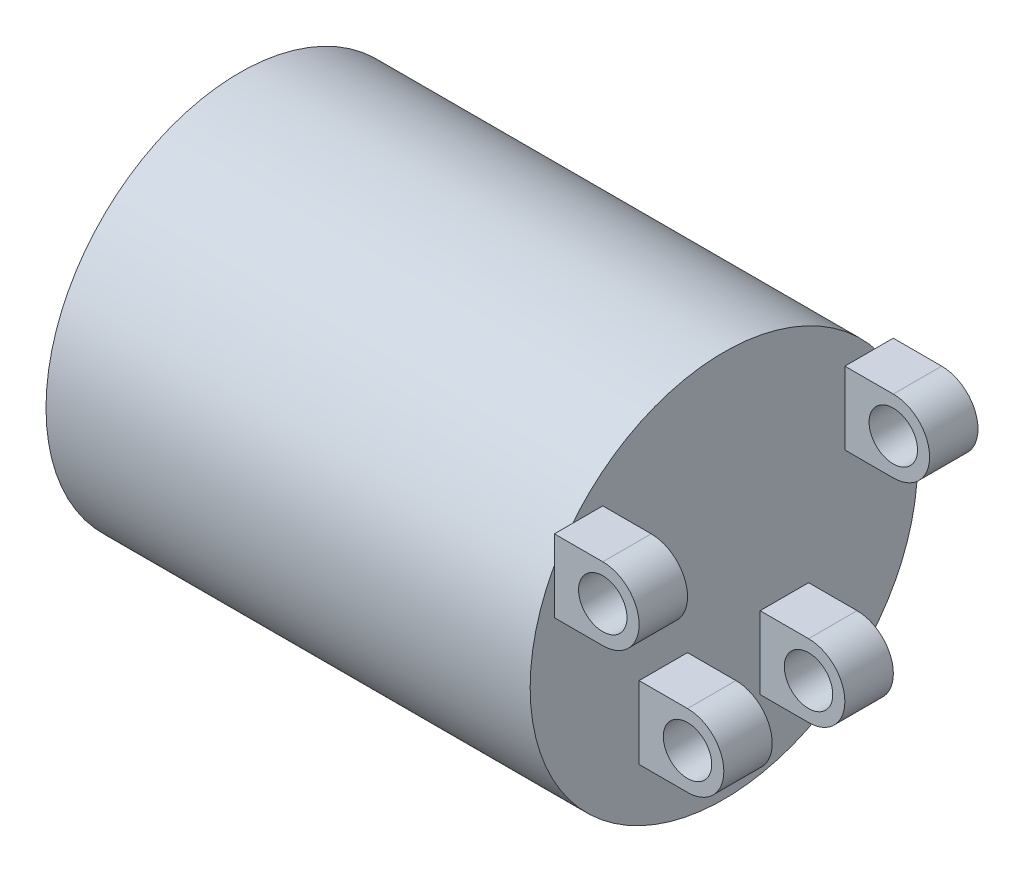
SolidWorks part; units mm, degrees
ref_plane "前视基准面" through (0, 0, 0) normal (0, 0, 1) x (1, 0, 0)
ref_plane "上视基准面" through (0, 0, 0) normal (0, 1, 0) x (1, 0, 0)
ref_plane "右视基准面" through (0, 0, 0) normal (1, 0, 0) x (0, 0, -1)
sketch "草图1" plane through (0, 0, 0) normal (1, 0, 0) x (0, 0, -1)
  circle A0 centre (0, 0) radius 40
extrude "凸台-拉伸1" add sketch "草图1" against normal blind 50 and the other way blind 50
sketch "草图2" plane through (50, 0, 0) normal (1, 0, 0) x (0, 0, -1)
  line L0 (-1000, 0) -> (49000, 0) construction
  line L1 (0, -1000) -> (0, 15) construction
  line L2 (-25, 0) -> (-25, 15)
  line L3 (25, 0) -> (25, 15)
  line L4 (7.5, -15) -> (7.5, 0)
  line L5 (-7.5, -15) -> (-7.5, 0)
  line L6 (7.5, -15) -> (17.5185, -15)
  line L7 (-25, 25) -> (-35, 25)
  line L8 (-17.5, -15) -> (-7.5, -15)
  line L9 (-35, 15) -> (-25, 15)
  line L10 (-25, 25) -> (-25, 10)
  line L11 (-25, 10) -> (-35, 10)
  line L12 (-35, 25) -> (-35, 10)
  line L13 (25, 25) -> (35, 25)
  line L14 (25, 25) -> (25, 10)
  line L15 (25, 10) -> (35, 10)
  line L16 (35, 25) -> (35, 10)
  line L17 (-7.5, -10) -> (-17.5, -10)
  line L18 (-7.5, -10) -> (-7.5, -25)
  line L19 (-7.5, -25) -> (-17.5, -25)
  line L20 (-17.5, -10) -> (-17.5, -25)
  line L21 (7.5, -10) -> (17.5185, -10)
  line L22 (7.5, -10) -> (7.5, -25)
  line L23 (7.5, -25) -> (17.5185, -25)
  line L24 (17.5185, -10) -> (17.5185, -25)
  line L25 (-1000, -15) -> (49000, -15) construction
  line L26 (-1000, 15) -> (49000, 15) construction
  line L27 (-25, -1000) -> (-25, 49000) construction
  line L28 (25, -1000) -> (25, 49000) construction
  line L29 (7.5, -1000) -> (7.5, 49000) construction
  line L30 (-7.5, -1000) -> (-7.5, 49000) construction
  line L31 (25, 15) -> (35, 15)
  line L32 (0, -1000) -> (0, 49000) construction
  point P4 (0, 0)
  dimension "D1" = 25
  dimension "D2" = 25
  dimension "D3" = 7.5
  dimension "D4" = 7.5
  dimension "D7" = 15
  dimension "D8" = 15
extrude "凸台-拉伸2" add sketch "草图2" along normal blind 10 separate body contours L16 L13 L3 L15 | L24 L21 L4 L6 | L17 L20 L8 L5 | L7 L12 L11 L2
sketch "草图4" plane through (60, 0, 0) normal (1, 0, 0) x (0, 0, -1)
  line L0 (-25, 25) -> (-25, 10) construction
  line L1 (-35, 25) -> (-25, 25)
  line L2 (-35, 25) -> (-35, 17.5)
  line L3 (-35, 17.5) -> (-25, 17.5)
  line L4 (-25, 25) -> (-25, 17.5)
revolve "旋转1" add sketch "草图4" angle 360 about L3
sketch "草图5" plane through (60, 0, 0) normal (1, 0, 0) x (0, 0, -1)
  line L0 (35, 25) -> (35, 10) construction
  line L1 (25, 25) -> (35, 25)
  line L2 (25, 25) -> (25, 17.5)
  line L3 (25, 17.5) -> (35, 17.5)
  line L4 (35, 25) -> (35, 17.5)
revolve "旋转2" add sketch "草图5" angle 360 about L3
sketch "草图6" plane through (60, 0, 0) normal (1, 0, 0) x (0, 0, -1)
  line L0 (-7.5, -10) -> (-7.5, -25) construction
  line L1 (-17.5, -10) -> (-7.5, -10)
  line L2 (-17.5, -10) -> (-17.5, -17.5)
  line L3 (-17.5, -17.5) -> (-7.5, -17.5)
  line L4 (-7.5, -10) -> (-7.5, -17.5)
revolve "旋转3" add sketch "草图6" angle 360 about L3
sketch "草图7" plane through (60, 0, 0) normal (1, 0, 0) x (0, 0, -1)
  line L0 (17.5185, -10) -> (17.5185, -25) construction
  line L1 (7.5, -10) -> (17.5185, -10)
  line L2 (7.5, -10) -> (7.5, -17.5)
  line L3 (7.5, -17.5) -> (17.5185, -17.5)
  line L4 (17.5185, -10) -> (17.5185, -17.5)
revolve "旋转4" add sketch "草图7" angle 360 about L3
ref_plane "基准面1" through (60, 25, 35) normal (-1, 0, 0) x (0, 0, 1)
sketch "草图9" plane through (0, 0, 35) normal (0, 0, 1) x (1, 0, 0)
  circle A0 centre (60, 17.5) radius 5
extrude "切除-拉伸1" cut sketch "草图9" against normal through all both and the other way through all
sketch "草图10" plane through (0, 0, 17.5) normal (0, 0, 1) x (1, 0, 0)
  circle A0 centre (60, -17.5) radius 5
extrude "切除-拉伸2" cut sketch "草图10" against normal through all both and the other way through all
